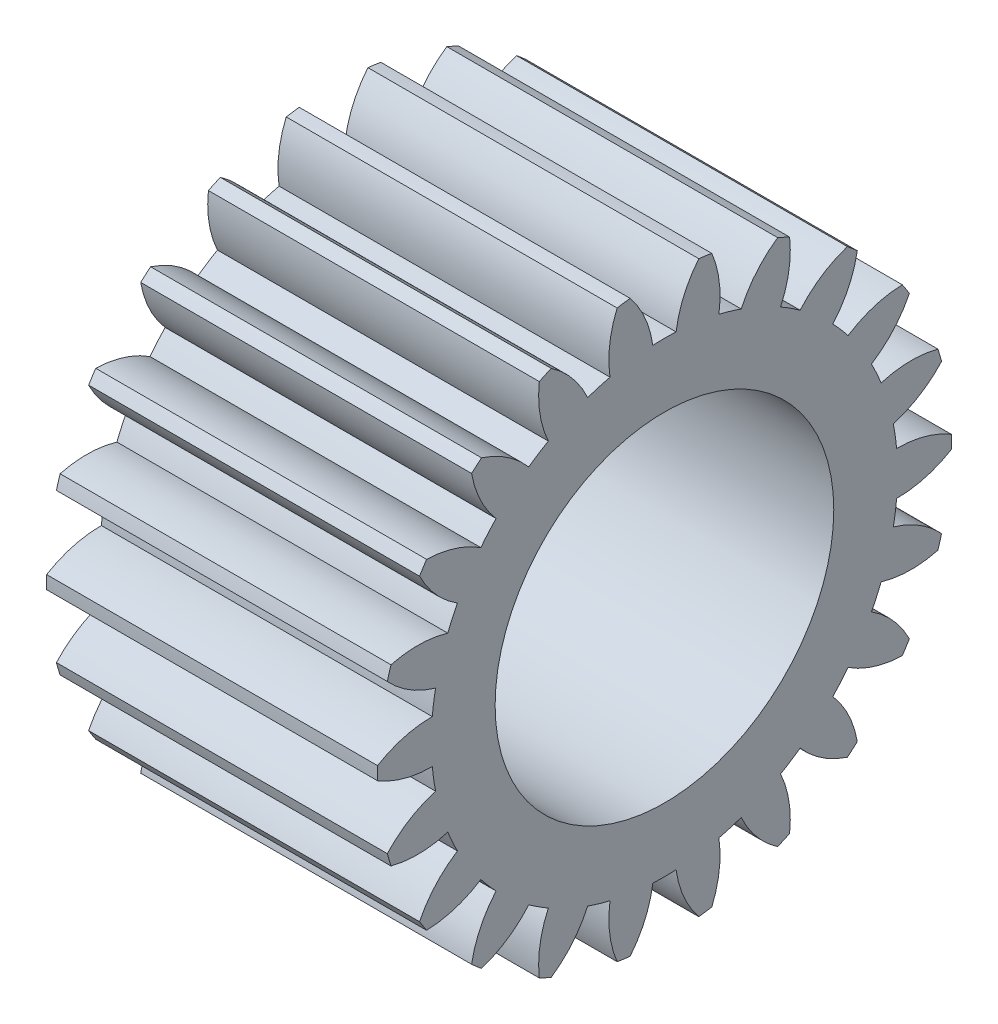
SolidWorks part; units mm, degrees
ref_plane "Plane1" through (0, 0, 0) normal (0, 0, 1) x (1, 0, 0)
ref_plane "Plane2" through (0, 0, 0) normal (0, 1, 0) x (1, 0, 0)
ref_plane "Plane3" through (0, 0, 0) normal (1, 0, 0) x (0, 0, -1)
other "Configuration Table"
sketch "HoldingSke" plane through (0, 0, 0) normal (0, 1, 0) x (1, 0, 0)
  line L0 (0, 0) -> (0.3709, -0.1498)
  line L1 (-15, 0) -> (100, 0) construction
  line L2 (0, 0) -> (-2.1039, 2.3779)
  line L3 (0, 0) -> (-11.863, 4.5341)
  line L4 (0, 0) -> (8.0072, 3.2351)
  line L5 (0, 0) -> (-46.8476, -17.4728)
  line L6 (0, 0) -> (-36.8888, -24.889)
  line L7 (-2.1039, 2.3779) -> (8.6586, 51.2059)
  line L8 (-76.2, 54.61) -> (-72.9, 54.61)
  line L9 (-71.009, 38.7566) -> (-53.1078, 45.2721)
  line L10 (-76.2, 71.12) -> (104.1128, 71.12)
  line L11 (0, 0) -> (-44.5, 0)
  line L12 (-76.2, 101.6) -> (-76.113, 101.6)
  line L13 (24.9733, 27.94) -> (52.9518, 28.4284)
  line L14 (24.9733, 27.94) -> (24.9743, 27.94)
  line L15 (24.9733, 27.94) -> (100.4006, 29.5858)
  line L16 (-63.627, -2.5) -> (-12.827, -2.5)
  circle A0 centre (0, 0) radius 12
  circle A1 centre (0, 0) radius 21
  circle A2 centre (0, 0) radius 21
  circle A3 centre (0, 0) radius 12
  dimension "MHD" = 42
  dimension "Hub_dia" = 42
  dimension "Bore" = 24
  dimension "MBD" = 24
  dimension "Num_teeth" = 22
  dimension "Pitch" = 0.4
  dimension "Overall_len" = 50
  dimension "Show_teeth" = 22
  dimension "Thickness" = 44.5
  dimension "OAL" = 50.0001
  dimension "T_dim" = 3.3
  dimension "Ap" = 20
  dimension "H" = 19.05
  dimension "Pitch_radius" = 180.3128
  dimension "Width" = 44.5
  dimension "Backlash" = 0.087
  dimension "Addendum_fac" = 1
  dimension "Dedendum_fac" = 1.25
  dimension "Clearance_fac" = 0.25
  dimension "Dedendum_add" = 0.001
  dimension "Module" = 2.5
sketch "BasProSke" plane through (0, 0, 0) normal (0, 1, 0) x (1, 0, 0)
  line L0 (-10, 0) -> (60, 0) construction
  line L1 (0, 0) -> (0, 30)
  line L2 (0, 0) -> (44.5, 0)
  line L3 (44.5, 0) -> (44.5, 30)
  line L4 (44.5, 30) -> (0, 30)
  dimension "Thickness" = 44.5
  dimension "Diameter" = 60
revolve "Base-Revolve" add sketch "BasProSke" angle 360 about L0
sketch "TooCutSke" plane through (0, 0, 0) normal (1, 0, 0) x (0, 0, -1)
  line L1 (0, 0) -> (0, 107) construction
  line L2 (0, 0) -> (-2.114, 27.4186) construction
  line L3 (0, 0) -> (-7.8104, 54.3222) construction
  line L4 (-2.114, 27.4186) -> (-3.9052, 27.1611) construction
  arc A0 (1.2153, 24.3437) -> (-1.2153, 24.3437) centre (0, 0) ccw
  arc A1 (3.6084, 29.8078) -> (-3.6084, 29.8078) centre (0, 0) ccw
  circle A2 centre (0, 0) radius 27.5 construction
  circle A3 centre (0, 0) radius 25.8415 construction
  arc A4 (-1.2153, 24.3437) -> (-3.6084, 29.8078) centre (-12.1104, 22.8281) ccw
  arc A5 (3.6084, 29.8078) -> (1.2153, 24.3437) centre (12.1104, 22.8281) ccw
  dimension "Root_dia" = 48.748
  dimension "Overcut_dia" = 60.0508
  dimension "Pitch_dia" = 55
  dimension "Base_dia" = 51.6831
  dimension "Flank_rad" = 11
  dimension "Half_ang" = 8.182
  dimension "Half_CT" = 1.8096
extrude "ToothCut" cut sketch "TooCutSke" along normal through all
fillet "Breaks" [suppressed] radius 0.05
fillet "RootFillets" [suppressed] radius 0.626
pattern_circular "TeethCuts" count 22 every 16.364 about axis through (-10, 0, 0) along (1, 0, 0) of "ToothCut", "RootFillets", "Breaks"
sketch "HubNeaOneSke" plane through (0, 0, 0) normal (-1, 0, 0) x (0, 0, 1)
  circle A0 centre (0, 0) radius 21
  dimension "Diameter" = 42
extrude "HubNearOne" add sketch "HubNeaOneSke" along normal blind 5.5001
sketch "HubNeaBotSke" plane through (0, 0, 0) normal (-1, 0, 0) x (0, 0, 1)
  circle A0 centre (0, 0) radius 21
  dimension "Diameter" = 42
extrude "HubNearBoth" [suppressed] add sketch "HubNeaBotSke" along normal blind 2.75
ref_plane "FarPln" through (44.5, 0, 0) normal (1, 0, 0) x (0, 0, -1)
sketch "HubFarSke" plane through (44.5, 0, 0) normal (1, 0, 0) x (0, 0, -1)
  circle A0 centre (0, 0) radius 21
  dimension "Diameter" = 42
extrude "HubFar" [suppressed] add sketch "HubFarSke" along normal blind 2.75
sketch "BorSke" plane through (0, 0, 0) normal (1, 0, 0) x (0, 0, -1)
  circle A0 centre (0, 0) radius 12
  dimension "Diameter" = 24
extrude "Bore" cut sketch "BorSke" along normal mid plane 100.0001
sketch "KeySke" plane through (0, 0, 0) normal (1, 0, 0) x (0, 0, -1)
  line L0 (-4, 0) -> (-4, 15.3)
  line L1 (-4, 15.3) -> (4, 15.3)
  line L2 (4, 15.3) -> (4, 0)
  line L3 (0, 0) -> (0, 34) construction
  line L4 (-4, 0) -> (4, 0)
  dimension "Offset" = 15.3
  dimension "Width" = 8
extrude "Keyway" [suppressed] cut sketch "KeySke" along normal mid plane 100.0001
pattern_circular "Keyway2" [suppressed] count 2 every 90 about axis through (-10, 0, 0) along (1, 0, 0)
sketch "Sketch1" plane through (-5.5001, 0, 0) normal (-1, 0, 0) x (0, 0, 1)
  circle A0 centre (0, 0) radius 30
extrude "Cut-Extrude1" cut sketch "Sketch1" against normal blind 15.41
sketch "Sketch2" plane through (9.9099, 0, 0) normal (-1, 0, 0) x (0, 0, 1)
  circle A0 centre (0, 0) radius 12
extrude "Boss-Extrude1" add sketch "Sketch2" against normal blind 3.95
sketch "Sketch3" plane through (9.9099, 0, 0) normal (-1, 0, 0) x (0, 0, 1)
  circle A1 centre (0, 8) radius 1.26
  circle A2 centre (6.9282, 4) radius 1.26
  circle A3 centre (6.9282, -4) radius 1.26
  circle A4 centre (0, -8) radius 1.26
  circle A5 centre (-6.9282, -4) radius 1.26
  circle A6 centre (-6.9282, 4) radius 1.26
  point P15 (0, 0)
  dimension "D1" = 6
extrude "Cut-Extrude2" cut sketch "Sketch3" against normal through all
sketch "Sketch4" plane through (44.5, 0, 0) normal (1, 0, 0) x (0, 0, -1)
  circle A0 centre (0, 0) radius 17.7
extrude "Cut-Extrude3" cut sketch "Sketch4" against normal blind 30.64
equation "' \"Module@HoldingSke\" = 6.35"
equation "' \"Num_teeth@HoldingSke\" = 12"
equation "' \"Ap@HoldingSke\" =  20"
equation "' \"Ap@HoldingSke\" = 20"
equation "' \"Width@HoldingSke\" = 0.5 * 25.4"
equation "' \"Hub_dia@HoldingSke\"= 1 * 25.4"
equation "' \"Hub_dia@HoldingSke\" = 1 * 25.4"
equation "' \"Overall_len@HoldingSke\" = 1.0 * 25.4"
equation "' \"Bore@HoldingSke\" = 0.75 * 25.4"
equation "' \"T_dim@HoldingSke\" = 0.1 * 25.4"
equation "' \"Width@KeySke\" = 0.25 * 25.4"
equation "' \"Show_teeth@HoldingSke\" = 13"
equation "' \"Backlash@HoldingSke\" = 0.009 * 25.4"
equation "' \"Addendum_fac@HoldingSke\" = 1.0"
equation "' \"Dedendum_fac@HoldingSke\" = 1.25"
equation "' \"Dedendum_add@HoldingSke\" = 0.00005 * 25.4"
equation "' \"Clearance_fac@HoldingSke\" = 0.25"
equation "\"Pitch@HoldingSke\" = 1 / \"Module@HoldingSke\""
equation "\"Overcut_dia@TooCutSke\" = (\"Num_teeth@HoldingSke\" + 2 * \"Addendum_fac@HoldingSke\") / \"Pitch@HoldingSke\" + 0.002 * 25.4"
equation "\"Pitch_dia@TooCutSke\" = \"Num_teeth@HoldingSke\" / \"Pitch@HoldingSke\""
equation "\"Base_dia@TooCutSke\" = \"Num_teeth@HoldingSke\" / \"Pitch@HoldingSke\" * cos((\"Ap@HoldingSke\"  * 3.14159265 / 180))"
equation "\"Root_dia@TooCutSke\" = (\"Num_teeth@HoldingSke\" + 2) / \"Pitch@HoldingSke\" - 2 * (\"Addendum_fac@HoldingSke\" + \"Dedendum_fac@HoldingSke\") / \"Pitch@HoldingSke\" - \"Dedendum_add@HoldingSke\" * 2"
equation "\"Half_ang@TooCutSke\" = 180 / \"Num_teeth@HoldingSke\""
equation "\"Half_CT@TooCutSke\" = \"Num_teeth@HoldingSke\" / \"Pitch@HoldingSke\" * sin((3.14159265 / 2 / \"Num_teeth@HoldingSke\")) / 2 - 7 * \"Backlash@HoldingSke\" / 4"
equation "\"Flank_rad@TooCutSke\" = \"Num_teeth@HoldingSke\" / \"Pitch@HoldingSke\" / 5"
equation "\"Radius@RootFillets\" = \"Clearance_fac@HoldingSke\" / \"Pitch@HoldingSke\" + \"Dedendum_add@HoldingSke\""
equation "\"Break_rad@Breaks\" = 0.02 / \"Pitch@HoldingSke\""
equation "\"Thickness@HoldingSke\" = \"Width@HoldingSke\""
equation "\"OAL@HoldingSke\" = \"Thickness@HoldingSke\""
equation "\"MHD@HoldingSke\" = (\"Num_teeth@HoldingSke\" + 2) / \"Pitch@HoldingSke\" - 2 * (\"Addendum_fac@HoldingSke\" + \"Dedendum_fac@HoldingSke\")  / \"Pitch@HoldingSke\" - \"Dedendum_add@HoldingSke\" * 2"
equation "\"MBD@HoldingSke\" = (\"Num_teeth@HoldingSke\" + 2) / \"Pitch@HoldingSke\" - 2 * (\"Addendum_fac@HoldingSke\" + \"Dedendum_fac@HoldingSke\")  / \"Pitch@HoldingSke\" - \"Dedendum_add@HoldingSke\" * 2 - 0.002 * 25.4"
equation "\"MHD@HoldingSke\" = ((sgn( \"MHD@HoldingSke\" - \"Hub_dia@HoldingSke\" )-1)*( \"MHD@HoldingSke\" - \"Hub_dia@HoldingSke\" ))/-2+ \"Hub_dia@HoldingSke\""
equation "\"MBD@HoldingSke\" = ((sgn( \"MBD@HoldingSke\" - \"Bore@HoldingSke\" )-1)*( \"MBD@HoldingSke\" - \"Bore@HoldingSke\" ))/-2+ \"Bore@HoldingSke\""
equation "\"OAL@HoldingSke\" = ((sgn( \"OAL@HoldingSke\" - \"Overall_len@HoldingSke\" )+1)*( \"OAL@HoldingSke\" - \"Overall_len@HoldingSke\" ))/2 + \"Overall_len@HoldingSke\" + 0.000002 * 25.4"
equation "\"Num_teeth@TeethCuts\" = int( \"Show_teeth@HoldingSke\" ) + 1"
equation "\"Num_teeth@TeethCuts\" = ((sgn( \"Num_teeth@TeethCuts\" - \"Num_teeth@HoldingSke\" )-1)*( \"Num_teeth@TeethCuts\" - \"Num_teeth@HoldingSke\" ))/-2+ \"Num_teeth@HoldingSke\""
equation "\"Num_teeth@TeethCuts\" = ((sgn( \"Num_teeth@TeethCuts\" - 2.0)+1)*( \"Num_teeth@TeethCuts\" - 2.0))/2 +2.0"
equation "\"Angle@TeethCuts\" = 360.0 / \"Num_teeth@HoldingSke\""
equation "\"Diameter@BasProSke\" = (\"Num_teeth@HoldingSke\" + 2 * \"Addendum_fac@HoldingSke\") / \"Pitch@HoldingSke\""
equation "\"Thickness@BasProSke\"  = \"Thickness@HoldingSke\""
equation "' \"Fillet_rad@BasProSke\" =  \"Thickness@HoldingSke\" * 0.05"
equation "' \"Fillet_rad@BasProSke\" = \"Thickness@HoldingSke\" * 0.05"
equation "\"MHD@HoldingSke\" = ((sgn( \"MHD@HoldingSke\" - \"Root_dia@TooCutSke\" )-1)*( \"MHD@HoldingSke\" - \"Root_dia@TooCutSke\" ))/-2+ \"Root_dia@TooCutSke\""
equation "\"Diameter@HubNeaOneSke\" = \"MHD@HoldingSke\""
equation "\"Length@HubNearOne\" = \"OAL@HoldingSke\" - \"Thickness@BasProSke\""
equation "\"Diameter@HubNeaBotSke\" = \"MHD@HoldingSke\""
equation "\"Length@HubNearBoth\" = ( \"OAL@HoldingSke\" - \"Thickness@BasProSke\" ) / 2.0"
equation "\"Thickness@FarPln\" = \"Thickness@BasProSke\""
equation "\"Diameter@HubFarSke\" = \"MHD@HoldingSke\""
equation "\"Length@HubFar\" = ( \"OAL@HoldingSke\" - \"Thickness@BasProSke\" ) / 2.0"
equation "\"Diameter@BorSke\" = \"MBD@HoldingSke\""
equation "\"D1@Bore\" = \"OAL@HoldingSke\" * 2.0"
equation "\"D1@Keyway\" = \"OAL@HoldingSke\" * 2.0"
equation "\"Offset@KeySke\" = \"T_dim@HoldingSke\" + \"MBD@HoldingSke\" / 2.0"
